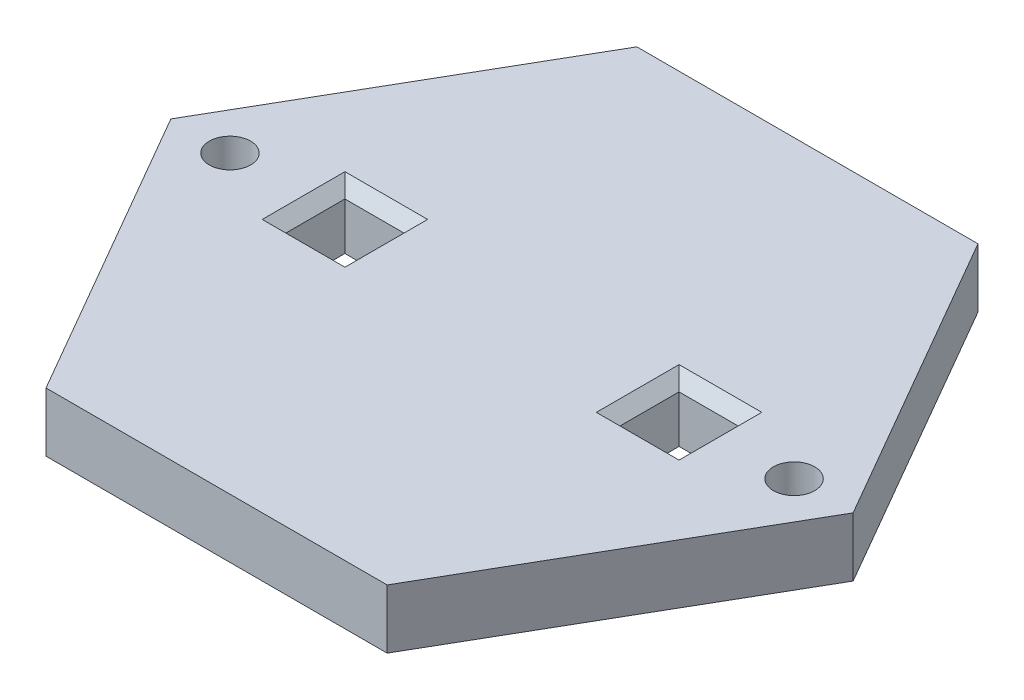
SolidWorks part; units mm, degrees
ref_plane "Front Plane" through (0, 0, 0) normal (0, 0, 1) x (1, 0, 0)
ref_plane "Top Plane" through (0, 0, 0) normal (0, 1, 0) x (1, 0, 0)
ref_plane "Right Plane" through (0, 0, 0) normal (1, 0, 0) x (0, 0, -1)
sketch "Sketch1" plane through (0, 0, 0) normal (0, 1, 0) x (1, 0, 0)
  line L1 (-28.8675, 0) -> (-14.4338, -25)
  line L2 (-14.4338, -25) -> (14.4338, -25)
  line L3 (14.4338, -25) -> (28.8675, 0)
  line L4 (28.8675, 0) -> (14.4338, 25)
  line L5 (14.4338, 25) -> (-14.4338, 25)
  line L6 (-14.4338, 25) -> (-28.8675, 0)
  circle A0 centre (0, 0) radius 25 construction
  dimension "D1" = 50
extrude "Boss-Extrude1" add sketch "Sketch1" along normal blind 5
sketch "Sketch2" plane through (0, 5, 0) normal (0, 1, 0) x (1, 0, 0)
  line L1 (-16.6375, 2.5) -> (-11.6375, 2.5)
  line L2 (-16.6375, 2.5) -> (-16.6375, -2.5)
  line L3 (-16.6375, -2.5) -> (-11.6375, -2.5)
  line L4 (-11.6375, 2.5) -> (-11.6375, -2.5)
  line L5 (-16.6375, 2.5) -> (-11.6375, -2.5) construction
  line L6 (-16.6375, -2.5) -> (-11.6375, 2.5) construction
  line L7 (11.6375, 2.5) -> (16.6375, 2.5)
  line L8 (11.6375, 2.5) -> (11.6375, -2.5)
  line L9 (11.6375, -2.5) -> (16.6375, -2.5)
  line L10 (16.6375, 2.5) -> (16.6375, -2.5)
  line L11 (11.6375, 2.5) -> (16.6375, -2.5) construction
  line L12 (11.6375, -2.5) -> (16.6375, 2.5) construction
  circle A0 centre (-23.8675, 0) radius 1.75
  circle A1 centre (23.8675, 0) radius 1.75
  point P4 (-14.1375, 0)
  point P9 (14.1375, 0)
  point P18 (-16.9369, 0.2282)
  dimension "D1" = 3.5
  dimension "D2" = 3.5
  dimension "D3" = 5
  dimension "D4" = 5
  dimension "D5" = 5
  dimension "D6" = 5
  dimension "D7" = 14.73
  dimension "D8" = 0
  dimension "D9" = 5
  dimension "D10" = 5
  dimension "D11" = 14.73
  dimension "D12" = 0
extrude "Cut-Extrude1" cut sketch "Sketch2" against normal blind 5
chamfer "Chamfer1" distance 1 angle 45 8 edges at (14.1375, 5, 2.5) (16.6375, 5, 0) (11.6375, 5, 0) (14.1375, 5, -2.5) (-14.1375, 5, 2.5) (-11.6375, 5, 0) (-16.6375, 5, 0) (-14.1375, 5, -2.5)
